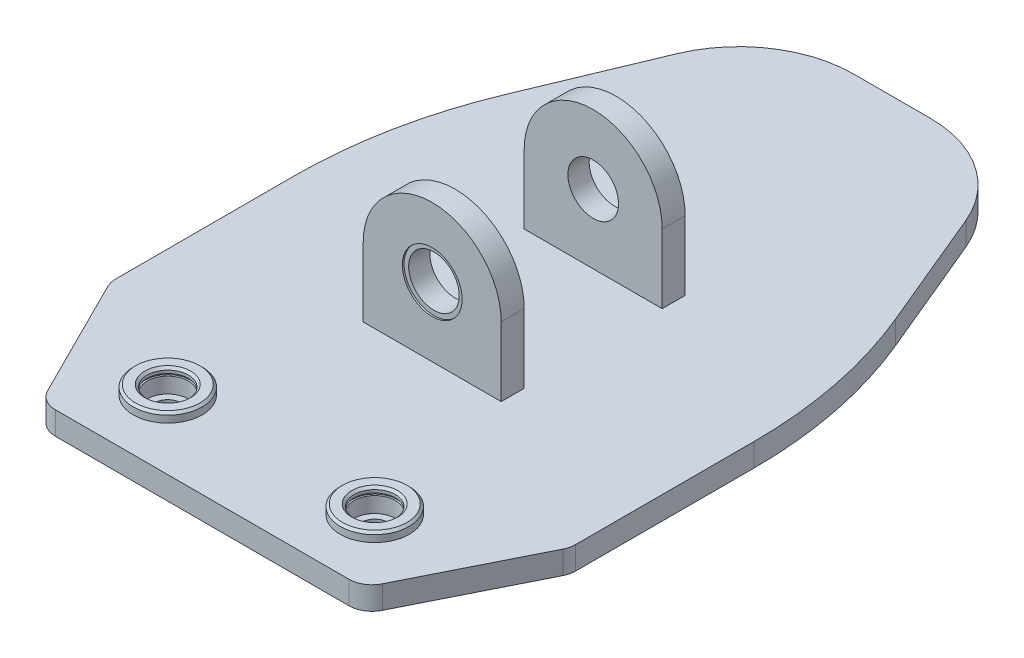
SolidWorks part; units mm, degrees
ref_plane "前视基准面" through (0, 0, 0) normal (0, 0, 1) x (1, 0, 0)
ref_plane "上视基准面" through (0, 0, 0) normal (0, 1, 0) x (1, 0, 0)
ref_plane "右视基准面" through (0, 0, 0) normal (1, 0, 0) x (0, 0, -1)
other "Configuration Table"
sketch "草图1" plane through (0, 0, 0) normal (0, 1, 0) x (1, 0, 0)
  line L0 (0, 0) -> (0, 255.8207) construction
  line L1 (-100, 0) -> (100, 0)
  line L2 (100, 0) -> (100, 180)
  line L3 (100, 180) -> (50, 300)
  line L4 (50, 300) -> (-50, 300)
  line L5 (-100, 180) -> (-50, 300)
  line L6 (-100, 0) -> (-100, 180)
  point P8 (0, 300)
  dimension "D1" = 300
  dimension "D2" = 100
  dimension "D3" = 120
  dimension "D4" = 50
extrude "凸台-拉伸1" add sketch "草图1" along normal blind 10
sketch "草图2" plane through (100, 0, 0) normal (1, 0, 0) x (0, 0, -1)
  line L0 (40, 100) -> (40, -10.3339) construction
  line L1 (0, 10) -> (0, 0) construction
  line L2 (0, 10) -> (0, 60)
  line L3 (80, 10) -> (80, 60)
  arc A0 (80, 60) -> (0, 60) centre (40, 60) ccw
  circle A1 centre (40, 60) radius 10
  line M6 (180, 10) -> (0, 10)
  dimension "D3" = 20
  dimension "D1" = 40
  dimension "D2" = 50
extrude "凸台-拉伸2" [suppressed] add sketch "草图2" against normal up to surface (200 mm away) contours A0 L0 A1 L3 M6 | L0 A0 L2 A1 M6
sketch "草图3" [suppressed] plane through (0, 10, 0) normal (0, 1, 0) x (1, 0, 0)
  line L0 (0, 0) -> (0, 135.8056) construction
  line L1 (-100, 0) -> (100, 0) construction
  line L2 (-70, 0) -> (70, 0)
  line L3 (-70, 0) -> (-70, 100)
  line L4 (-70, 100) -> (70, 100)
  line L5 (70, 0) -> (70, 100)
  line L6 (100, 0) -> (100, 80) construction
  line L7 (-100, 80) -> (-100, 0) construction
  dimension "D1" = 30
  dimension "D2" = 30
  dimension "D3" = 100
extrude "切除-拉伸1" [suppressed] cut sketch "草图3" along normal blind 171
sketch "草图4" plane through (0, 0, 0) normal (0, 0, 1) x (1, 0, 0)
  line L0 (0, 0) -> (0, 92.3322) construction
  line L1 (30, 40) -> (30, 10)
  line L2 (-30, 40) -> (-30, 10)
  line L3 (-100, 10) -> (100, 10) construction
  arc A0 (-30, 40) -> (30, 40) centre (0, 40) cw
  circle A1 centre (0, 40) radius 11
  line M10 (100, 10) -> (-100, 10)
  dimension "D2" = 30
  dimension "D3" = 22
  dimension "D1" = 30
extrude "凸台-拉伸3" add sketch "草图4" against normal blind 80 from offset 100 contours L0 L1 A0 A1 M10 | L0 A1 A0 L2 M10 offset against normal yes
sketch "草图5" plane through (0, 10, 0) normal (0, 1, 0) x (1, 0, 0)
  line L0 (-47.074, 140) -> (51.1394, 140) construction
  line L1 (30, 180) -> (-30, 180) construction
  line L2 (30, 100) -> (-30, 100) construction
  line L3 (-30, 100) -> (30, 100) construction
  line L4 (-40, 170) -> (40, 170)
  line L5 (-40, 170) -> (-40, 110)
  line L6 (-40, 110) -> (40, 110)
  line L7 (40, 170) -> (40, 110)
  line L8 (30, 180) -> (30, 100) construction
  line L9 (-30, 180) -> (-30, 100) construction
  dimension "D1" = 10
  dimension "D2" = 10
  dimension "D3" = 10
  dimension "D4" = 10
extrude "切除-拉伸2" cut sketch "草图5" along normal blind 110 contours L7 L6 L5 L4
fillet "圆角1" radius 50 2 edges at (-50, 5, -300) (50, 5, -300)
fillet "圆角2" radius 200 2 edges at (-100, 5, -180) (100, 5, -180)
sketch "草图6" [suppressed] plane through (100, 0, 0) normal (1, 0, 0) x (0, 0, -1)
  line L0 (40, 60) -> (40, -52.2503) construction
  circle A0 centre (40, 60) radius 10 construction
  circle A1 centre (40, 60) radius 10 construction
  arc A2 (73.0468, 82.5368) -> (6.9532, 82.5368) centre (40, -25) ccw
  arc A3 (80, 60) -> (0, 60) centre (40, 60) ccw construction
  arc A4 (73.0468, 82.5368) -> (6.9532, 82.5368) centre (40, 60) ccw
  dimension "D2" = 225
  dimension "D1" = 25
extrude "切除-拉伸3" [suppressed] cut sketch "草图6" against normal through all both and the other way through all contours A2 A4
sketch "草图7" plane through (0, 10, 0) normal (0, 1, 0) x (1, 0, 0)
  line L0 (0, 0) -> (0, 141.3983) construction
  line L1 (-100, 0) -> (100, 0) construction
  circle A0 centre (45, 30) radius 9
  dimension "D1" = 18
  dimension "D2" = 45
  dimension "D3" = 30
extrude "切除-拉伸6" cut sketch "草图7" against normal offset from surface (6 mm away) 4 contours A0 up to face at (0, 0, -186.7805)
sketch "草图10" plane through (0, 4, 0) normal (0, 1, 0) x (1, 0, 0)
  circle A0 centre (45, 30) radius 6
  dimension "D1" = 12
extrude "切除-拉伸7" cut sketch "草图10" against normal blind 28 contours A0
sketch "草图11" plane through (0, 10, 0) normal (0, 1, 0) x (1, 0, 0)
  circle A0 centre (45, 30) radius 12.5
  circle A1 centre (45, 30) radius 16.5
  dimension "D1" = 25
  dimension "D2" = 33
extrude "切除-拉伸8" [suppressed] cut sketch "草图11" against normal blind 5
sketch "草图12" plane through (0, 10, 0) normal (0, 1, 0) x (1, 0, 0)
  circle A0 centre (45, 30) radius 15
  dimension "D1" = 30
extrude "凸台-拉伸5" add sketch "草图12" along normal blind 4 contours A0
sketch "草图13" plane through (0, 14, 0) normal (0, 1, 0) x (1, 0, 0)
  circle A0 centre (45, 30) radius 9
  dimension "D1" = 18
extrude "切除-拉伸9" cut sketch "草图13" against normal blind 4
sketch "草图14" plane through (0, 14, 0) normal (0, 1, 0) x (1, 0, 0)
  circle A0 centre (45, 30) radius 9.75
  circle A2 centre (45, 30) radius 9 construction
  circle A3 centre (45, 30) radius 9
  dimension "D1" = 19.5
extrude "卡簧槽" cut sketch "草图14" against normal blind 1 from offset 2.25 contours A0 offset against normal yes
chamfer "倒角1" distance 1 angle 45 2 edges at (45, 14, -15) (45, 14, -21)
ref_plane "基准面1" through (0, 0, 0) normal (-1, 0, 0) x (0, 0, 1)
mirror "镜向1" about plane through (0, 0, 0) normal (-1, 0, 0) of "切除-拉伸6", "切除-拉伸7", "凸台-拉伸5", "切除-拉伸9", "卡簧槽", "倒角1"
sketch "草图16" plane through (0, 0, -100) normal (0, 0, 1) x (1, 0, 0)
  circle A0 centre (0, 40) radius 13
  dimension "D1" = 26
extrude "切除-拉伸10" cut sketch "草图16" against normal blind 0.75
sketch "草图17" plane through (0, 0, -180) normal (0, 0, -1) x (-1, 0, 0)
  circle A0 centre (0, 40) radius 13
  dimension "D1" = 26
extrude "切除-拉伸11" cut sketch "草图17" against normal blind 0.75 contours A0
sketch "草图18" plane through (-100, 0, 0) normal (-1, 0, 0) x (0, 0, 1)
  line L0 (-30, 92.2697) -> (-30, -20.0308) construction
  line L1 (-40, 10) -> (-40, 30)
  line L2 (-140, 10) -> (0, 10) construction
  line L3 (-20, 30) -> (-20, 10)
  line L4 (-40, 10) -> (-20, 10)
  arc A0 (-20, 30) -> (-40, 30) centre (-30, 30) ccw
  circle A1 centre (-30, 30) radius 2.5
  dimension "D2" = 5
  dimension "D4" = 10
  dimension "D1" = 30
  dimension "D3" = 20
extrude "凸台-拉伸6" [suppressed] add sketch "草图18" against normal up to surface (200 mm away) contours A1 L0 | L0 A1 | L3 L4 L1 A0
sketch "草图20" plane through (0, 10, 0) normal (0, 1, 0) x (1, 0, 0)
  line L0 (0, 0) -> (0, 309.5578) construction
  line L1 (-100, 0) -> (100, 0) construction
  line L2 (-60.0864, 49.2403) -> (-60.0864, 11.6041)
  line L3 (75.0864, 51.8093) -> (107.8414, 51.8093)
  line L4 (75.0864, 51.8093) -> (75.0864, 7.1083)
  line L5 (75.0864, 7.1083) -> (107.8414, 7.1083)
  line L6 (107.8414, 51.8093) -> (107.8414, 7.1083)
  line L7 (15, 49.2403) -> (60.0864, 49.2403)
  line L8 (15, 49.2403) -> (15, 11.6041)
  line L9 (15, 11.6041) -> (60.0864, 11.6041)
  line L10 (60.0864, 49.2403) -> (60.0864, 11.6041)
  line L11 (-15, 11.6041) -> (-60.0864, 11.6041)
  line L12 (-15, 49.2403) -> (-15, 11.6041)
  line L13 (-15, 49.2403) -> (-60.0864, 49.2403)
  line L14 (-107.8414, 51.8093) -> (-107.8414, 7.1083)
  line L15 (-75.0864, 7.1083) -> (-107.8414, 7.1083)
  line L16 (-75.0864, 51.8093) -> (-75.0864, 7.1083)
  line L17 (-75.0864, 51.8093) -> (-107.8414, 51.8093)
  dimension "D1" = 15
  dimension "D2" = 15
extrude "切除-拉伸12" [suppressed] cut sketch "草图20" along normal through all
chamfer "倒角2" distance 30 distance2 60 1 edges at (100, 5, 0)
chamfer "倒角3" distance 60 distance2 30 1 edges at (-100, 5, 0)
fillet "圆角3" radius 10 4 edges at (-70, 5, 0) (-100, 5, -60) (70, 5, 0) (100, 5, -60)
ref_plane "脚底板中心面" through (0, 0, 0) normal (-1, 0, 0) x (0, 0, 1)
ref_plane "基准面3" through (0, 0, -30) normal (0, 0, 1) x (1, 0, 0)
sketch "草图22" plane through (0, 0, -30) normal (0, 0, 1) x (1, 0, 0)
  line L0 (45, 18.5577) -> (45, -23.1228) construction
  line L1 (-45, 24.8334) -> (-45, -23.1228) construction
  line L2 (45, 0) -> (45, 4) construction
  line L3 (-45, 0) -> (-45, 4) construction
ref_plane "基准面4" through (-45, 0, 0) normal (-1, 0, 0) x (0, 0, 1)
